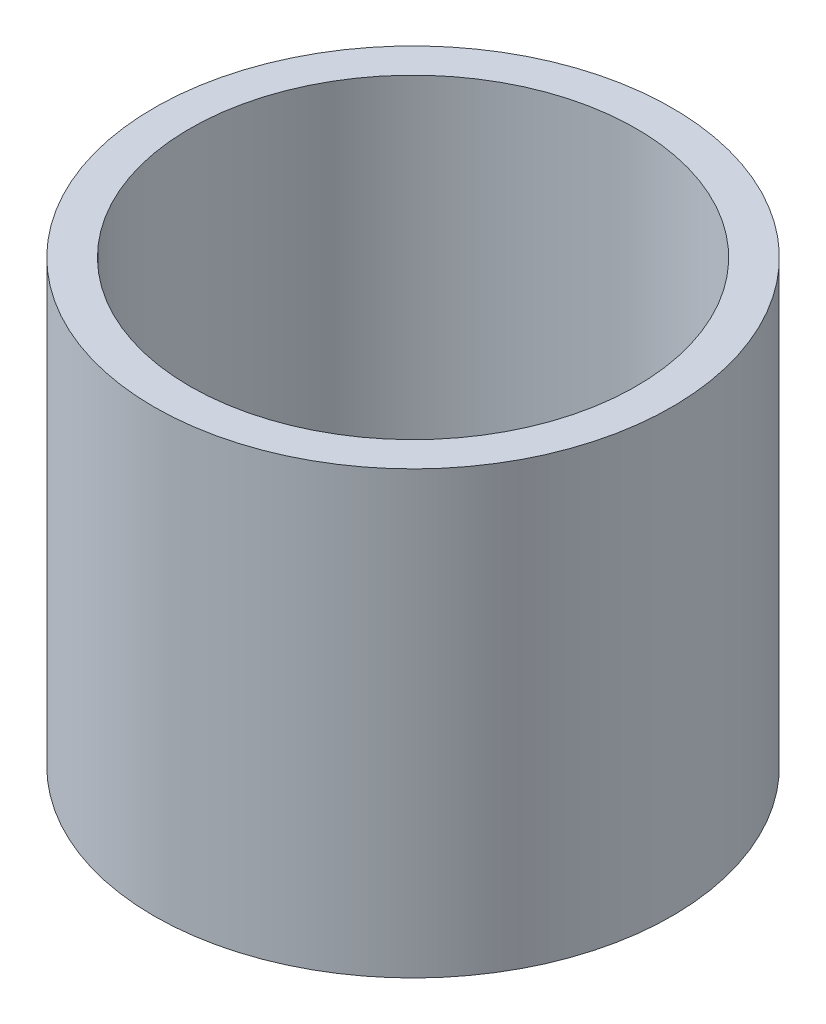
SolidWorks part; units mm, degrees
ref_plane "Alzado" through (0, 0, 0) normal (0, 0, 1) x (1, 0, 0)
ref_plane "Planta" through (0, 0, 0) normal (0, 1, 0) x (1, 0, 0)
ref_plane "Vista lateral" through (0, 0, 0) normal (1, 0, 0) x (0, 0, -1)
sketch "Sketch1" plane through (0, 0, 0) normal (0, 1, 0) x (1, 0, 0)
  circle A0 centre (0, 0) radius 4.7
  circle A1 centre (0, 0) radius 4.05
  dimension "D1" = 9.4
  dimension "D2" = 8.1
extrude "Boss-Extrude1" add sketch "Sketch1" along normal blind 8
